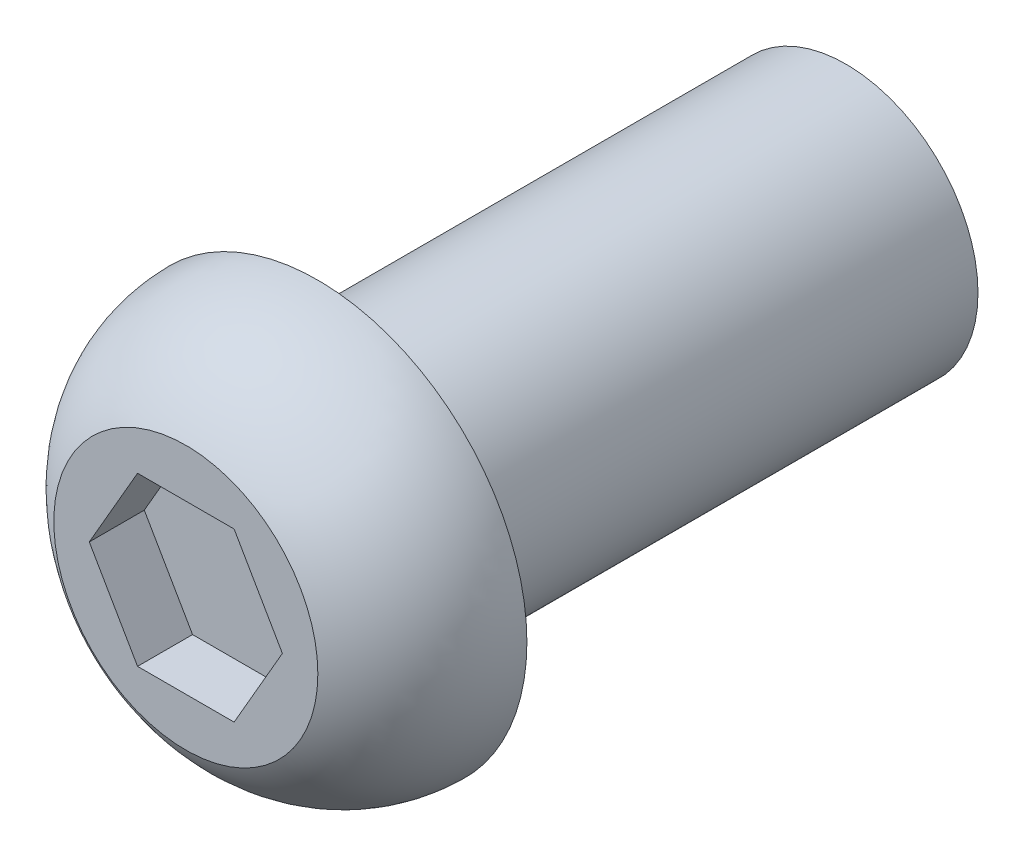
SolidWorks part; units mm, degrees
ref_plane "前视基准面" through (0, 0, 0) normal (0, 0, 1) x (1, 0, 0)
ref_plane "上视基准面" through (0, 0, 0) normal (0, 1, 0) x (1, 0, 0)
ref_plane "右视基准面" through (0, 0, 0) normal (1, 0, 0) x (0, 0, -1)
sketch "草图1" plane through (0, 0, 0) normal (1, 0, 0) x (0, 0, -1)
  line L0 (0, 0) -> (30, 0) construction
  line L1 (30, 0) -> (30, 6)
  line L2 (30, 6) -> (6, 6)
  line L3 (6, 6) -> (6, 9.5)
  line L4 (6, 9.5) -> (0, 9.5)
  line L5 (0, 9.5) -> (0, 0)
  arc A1 (6, 9.5) -> (0, 6) centre (6, 2.6071) ccw
  dimension "L" = 30
  dimension "D" = 19
  dimension "H" = 6
  dimension "M" = 12
sketch "草图2" plane through (0, 0, 0) normal (1, 0, 0) x (0, 0, -1)
  line L0 (6, 9.5) -> (0, 9.5) construction
  line L5 (0, 9.5) -> (0, 0) construction
  line L6 (6, 6) -> (6, 9.5) construction
  line L7 (30, 6) -> (6, 6) construction
  line L8 (30, 0) -> (30, 6) construction
  line L9 (0, 0) -> (30, 0) construction
  line L10 (6, 9.5) -> (0, 9.5)
  line L11 (0, 9.5) -> (0, 0)
  line L12 (6, 6) -> (6, 9.5)
  line L13 (30, 6) -> (6, 6)
  line L14 (30, 0) -> (30, 6)
  line L15 (0, 0) -> (30, 0)
revolve "旋转1" add sketch "草图2" angle 360 mid plane about L15
cosmetic thread "装饰螺纹线1" parameters "D2"=11.9
sketch "草图3" plane through (0, 0, 0) normal (0, 0, 1) x (1, 0, 0)
  line L1 (2.1939, -3.8) -> (4.3879, 0)
  line L2 (4.3879, 0) -> (2.1939, 3.8)
  line L3 (2.1939, 3.8) -> (-2.1939, 3.8)
  line L4 (-2.1939, 3.8) -> (-4.3879, 0)
  line L5 (-4.3879, 0) -> (-2.1939, -3.8)
  line L6 (-2.1939, -3.8) -> (2.1939, -3.8)
  circle A0 centre (0, 0) radius 3.8 construction
  dimension "D1" = 7.6
extrude "切除-拉伸1" cut sketch "草图3" against normal blind 2.5
sketch "草图4" plane through (0, 0, 0) normal (1, 0, 0) x (0, 0, -1)
  line L0 (6, 9.5) -> (0, 9.5) construction
  line L1 (0, 9.5) -> (0, 0) construction
  line L2 (6, 9.5) -> (0, 9.5)
  line L3 (0, 9.5) -> (0, 6)
  arc A0 (6, 9.5) -> (0, 6) centre (6, 2.6071) ccw construction
  arc A1 (6, 9.5) -> (0, 6) centre (6, 2.6071) ccw
revolve "切除-旋转1" cut sketch "草图4" angle 360 mid plane about L0
